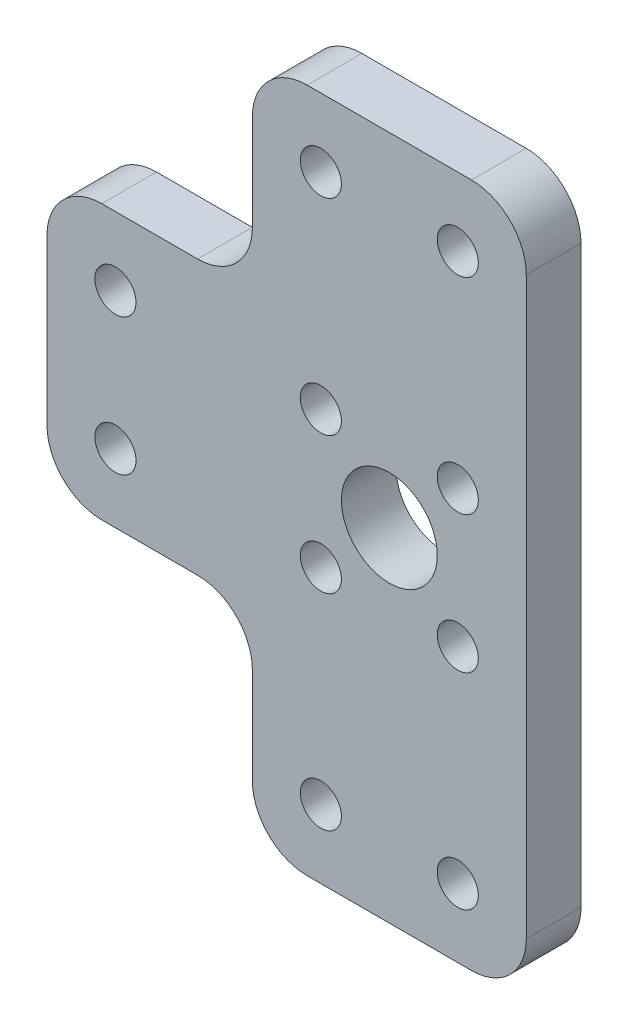
SolidWorks part; units mm, degrees
material "Thornel Mat VMA"
ref_plane "前视基准面" through (0, 0, 0) normal (0, 0, 1) x (1, 0, 0)
ref_plane "上视基准面" through (0, 0, 0) normal (0, 1, 0) x (1, 0, 0)
ref_plane "右视基准面" through (0, 0, 0) normal (1, 0, 0) x (0, 0, -1)
other "Configuration Table"
sketch "草图1" plane through (0, 0, 0) normal (0, 0, 1) x (1, 0, 0)
  line L1 (-25, 10) -> (10, 10)
  line L2 (-25, 10) -> (-25, -10)
  line L3 (-25, -10) -> (10, -10)
  line L5 (-25, 10) -> (25, -10) construction
  line L6 (-25, -10) -> (25, 10) construction
  line L7 (-10, 25) -> (10, 25)
  line L8 (-10, 25) -> (-10, -25)
  line L9 (-10, -25) -> (10, -25)
  line L10 (10, 25) -> (10, -25)
  line L11 (-10, 25) -> (10, -25) construction
  line L12 (-10, -25) -> (10, 25) construction
  circle A0 centre (0, 0) radius 3.5
  circle A1 centre (-5, -5) radius 1.5
  circle A2 centre (5, -5) radius 1.5
  circle A3 centre (5, 5) radius 1.5
  circle A4 centre (-5, 5) radius 1.5
  circle A5 centre (-5, -20) radius 1.5
  circle A6 centre (5, -20) radius 1.5
  circle A7 centre (5, 20) radius 1.5
  circle A8 centre (-5, 20) radius 1.5
  circle A9 centre (-20, 5) radius 1.5
  circle A10 centre (-20, -5) radius 1.5
  point P0 (0, 0)
  point P6 (0, 0)
  dimension "D7" = 5
  dimension "D8" = 5
  dimension "D9" = 7
  dimension "D12" = 3
  dimension "D13" = 5
  dimension "D14" = 5
  dimension "D15" = 5
  dimension "D16" = 5
  dimension "D17" = 5
  dimension "D1" = 20
  dimension "D2" = 50
  dimension "D3" = 20
  dimension "D4" = 50
  dimension "D18" = 5
  dimension "D5" = 2
  dimension "D6" = 2
  dimension "D10" = 2
  dimension "D11" = 2
extrude "凸台-拉伸1" add sketch "草图1" along normal blind 4 contours L8 L1 L2 L3 A10 A9 | L10 L1 L8 L3 A4 A3 A2 A1 A0 | L10 L7 L8 L1 A8 A7 | L10 L3 L8 L9 A6 A5
fillet "圆角1" radius 4 8 edges at (-25, -10, 2) (-25, 10, 2) (-10, 25, 2) (10, 25, 2) (10, -25, 2) (-10, -25, 2) (-10, -10, 2) (-10, 10, 2)
